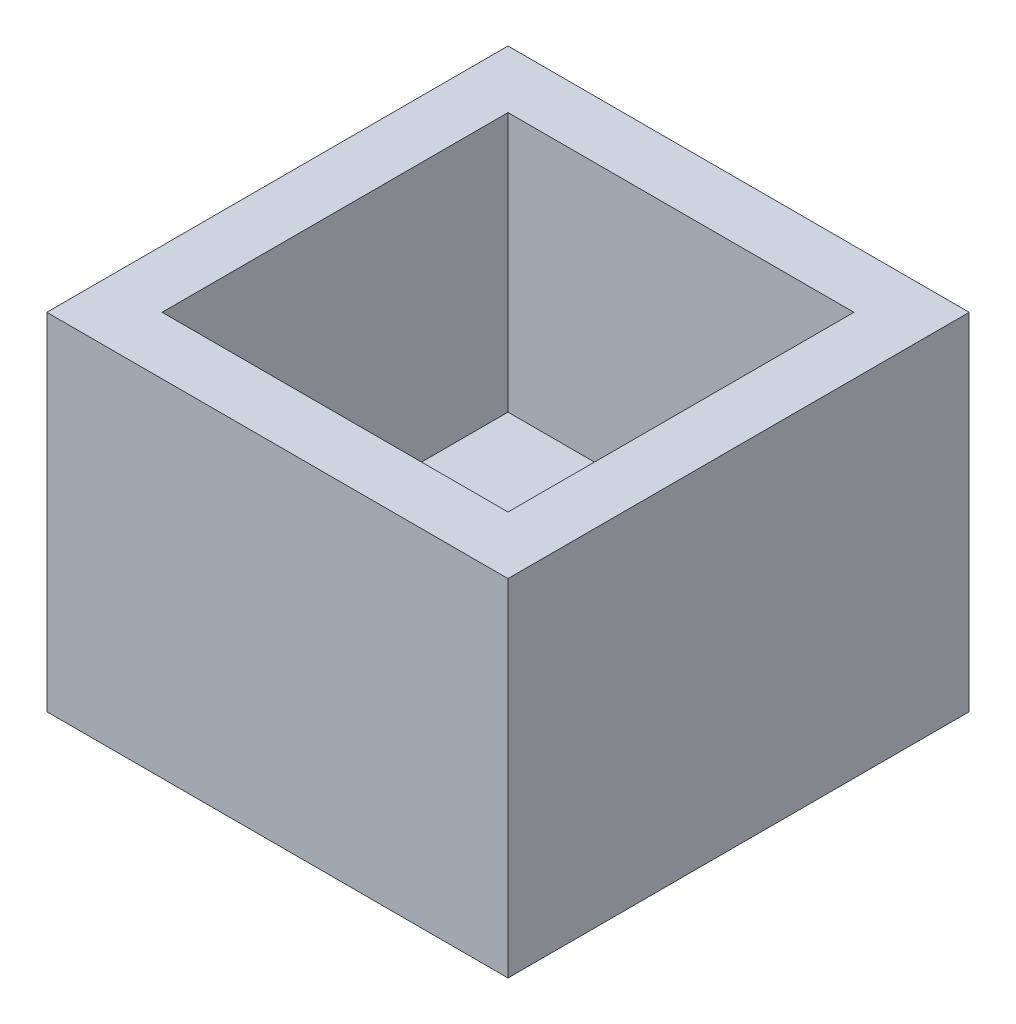
SolidWorks part; units mm, degrees
ref_plane "Front Plane" through (0, 0, 0) normal (0, 0, 1) x (1, 0, 0)
ref_plane "Top Plane" through (0, 0, 0) normal (0, 1, 0) x (1, 0, 0)
ref_plane "Right Plane" through (0, 0, 0) normal (1, 0, 0) x (0, 0, -1)
sketch "Sketch1" plane through (0, 0, 0) normal (0, 1, 0) x (1, 0, 0)
  line L1 (-50.8, -50.8) -> (50.8, -50.8)
  line L2 (-50.8, -50.8) -> (-50.8, 50.8)
  line L3 (-50.8, 50.8) -> (50.8, 50.8)
  line L4 (50.8, -50.8) -> (50.8, 50.8)
  line L5 (-50.8, -50.8) -> (50.8, 50.8) construction
  line L6 (-50.8, 50.8) -> (50.8, -50.8) construction
  point P0 (0, 0)
  dimension "D1" = 101.6
  dimension "D2" = 101.6
extrude "Boss-Extrude1" add sketch "Sketch1" along normal blind 76.2
sketch "Sketch3" plane through (0, 76.2, 0) normal (0, 1, 0) x (1, 0, 0)
  line L1 (-38.1, -38.1) -> (38.1, -38.1)
  line L2 (-38.1, -38.1) -> (-38.1, 38.1)
  line L3 (-38.1, 38.1) -> (38.1, 38.1)
  line L4 (38.1, -38.1) -> (38.1, 38.1)
  line L5 (-38.1, -38.1) -> (38.1, 38.1) construction
  line L6 (-38.1, 38.1) -> (38.1, -38.1) construction
  point P0 (0, 0)
  dimension "D1" = 76.2
  dimension "D2" = 76.2
extrude "Cut-Extrude2" cut sketch "Sketch3" against normal blind 57.15
